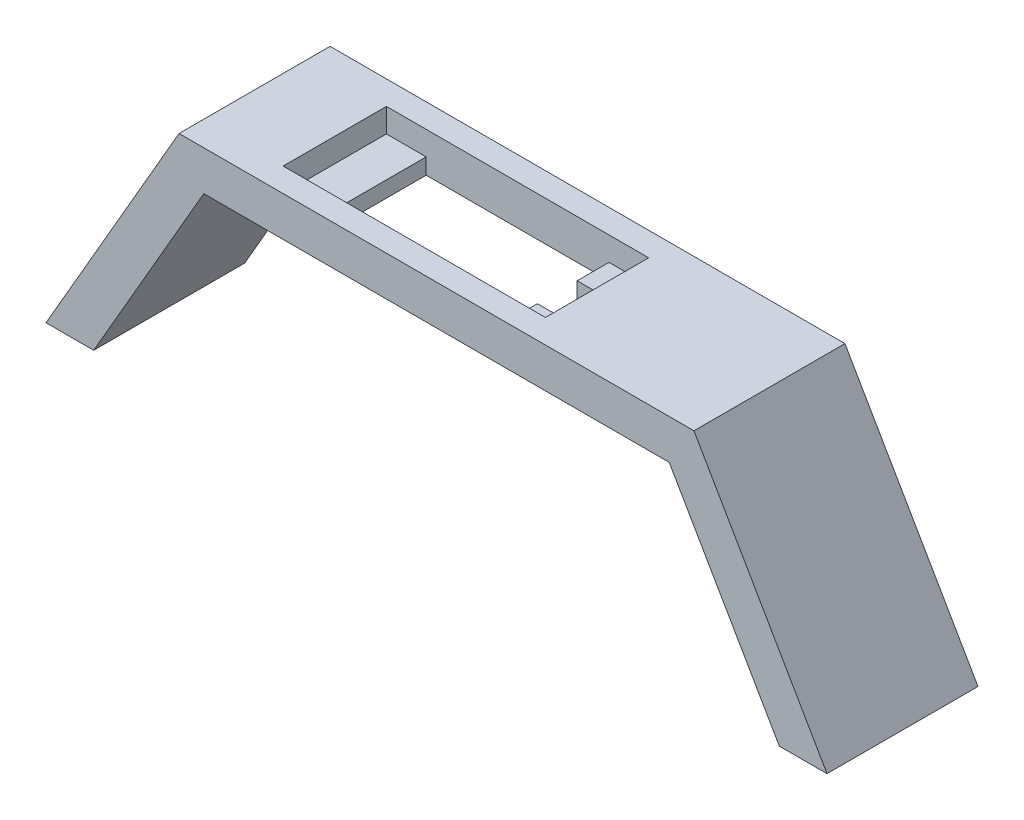
SolidWorks part; units mm, degrees
ref_plane "Front Plane" through (0, 0, 0) normal (0, 0, 1) x (1, 0, 0)
ref_plane "Top Plane" through (0, 0, 0) normal (0, 1, 0) x (1, 0, 0)
ref_plane "Right Plane" through (0, 0, 0) normal (1, 0, 0) x (0, 0, -1)
sketch "Sketch1" plane through (0, 0, 0) normal (0, 0, 1) x (1, 0, 0)
  line L0 (-29.2836, 0) -> (29.2836, 0)
  line L1 (29.2836, 0) -> (43.14, -24)
  line L2 (43.14, -24) -> (49.14, -24)
  line L3 (49.14, -24) -> (32.3968, 5)
  line L4 (32.3968, 5) -> (-32.3968, 5)
  line L5 (-32.3968, 5) -> (-49.14, -24)
  line L6 (-49.14, -24) -> (-43.14, -24)
  line L7 (-43.14, -24) -> (-29.2836, 0)
  point P6 (0, 0)
  dimension "D1" = 5
  dimension "D2" = 120
  dimension "D3" = 24
  dimension "D4" = 98.28
  dimension "D5" = 6
extrude "Boss-Extrude1" add sketch "Sketch1" along normal blind 19
sketch "Sketch2" plane through (0, 5, 0) normal (0, 1, 0) x (1, 0, 0)
  line L1 (10.7, -3) -> (-22.3, -3)
  line L2 (10.7, -3) -> (10.7, -16)
  line L3 (10.7, -16) -> (-22.3, -16)
  line L4 (-22.3, -3) -> (-22.3, -16)
  line L5 (10.7, -3) -> (-22.3, -16) construction
  line L6 (10.7, -16) -> (-22.3, -3) construction
  line L7 (32.3968, 0) -> (-32.3968, 0) construction
  point P0 (-5.8, -9.5)
  dimension "D1" = 33
  dimension "D2" = 13
  dimension "D3" = 10.7
  dimension "D4" = 3
extrude "Cut-Extrude1" cut sketch "Sketch2" against normal blind 3
sketch "Sketch3" plane through (0, 2, 0) normal (0, 1, 0) x (1, 0, 0)
  line L0 (-22.3, -16) -> (10.7, -16) construction
  line L1 (-17.3, -3) -> (5.7, -3)
  line L2 (-17.3, -3) -> (-17.3, -16)
  line L3 (-17.3, -16) -> (5.7, -16)
  line L4 (5.7, -3) -> (5.7, -16)
  line L5 (-17.3, -3) -> (5.7, -16) construction
  line L6 (-17.3, -16) -> (5.7, -3) construction
  line L7 (10.7, -3) -> (-22.3, -3) construction
  line L9 (10.7, -16) -> (10.7, -3) construction
  line L10 (-22.3, -3) -> (-22.3, -16) construction
  point P0 (-5.8, -9.5)
  dimension "D1" = 5
  dimension "D2" = 5
extrude "Cut-Extrude2" cut sketch "Sketch3" against normal up to next
sketch "Sketch4" plane through (0, 2, 0) normal (0, 1, 0) x (1, 0, 0)
  line L0 (5.7, -16) -> (5.7, -3) construction
  line L1 (10.7, -7) -> (5.7, -7)
  line L2 (10.7, -7) -> (10.7, -12)
  line L3 (10.7, -12) -> (5.7, -12)
  line L4 (5.7, -7) -> (5.7, -12)
  line L5 (10.7, -7) -> (5.7, -12) construction
  line L6 (10.7, -12) -> (5.7, -7) construction
  point P0 (8.2, -9.5)
  point P9 (5.7, -9.5)
  dimension "D1" = 5
  dimension "D2" = 5
extrude "Cut-Extrude3" cut sketch "Sketch4" against normal up to next
